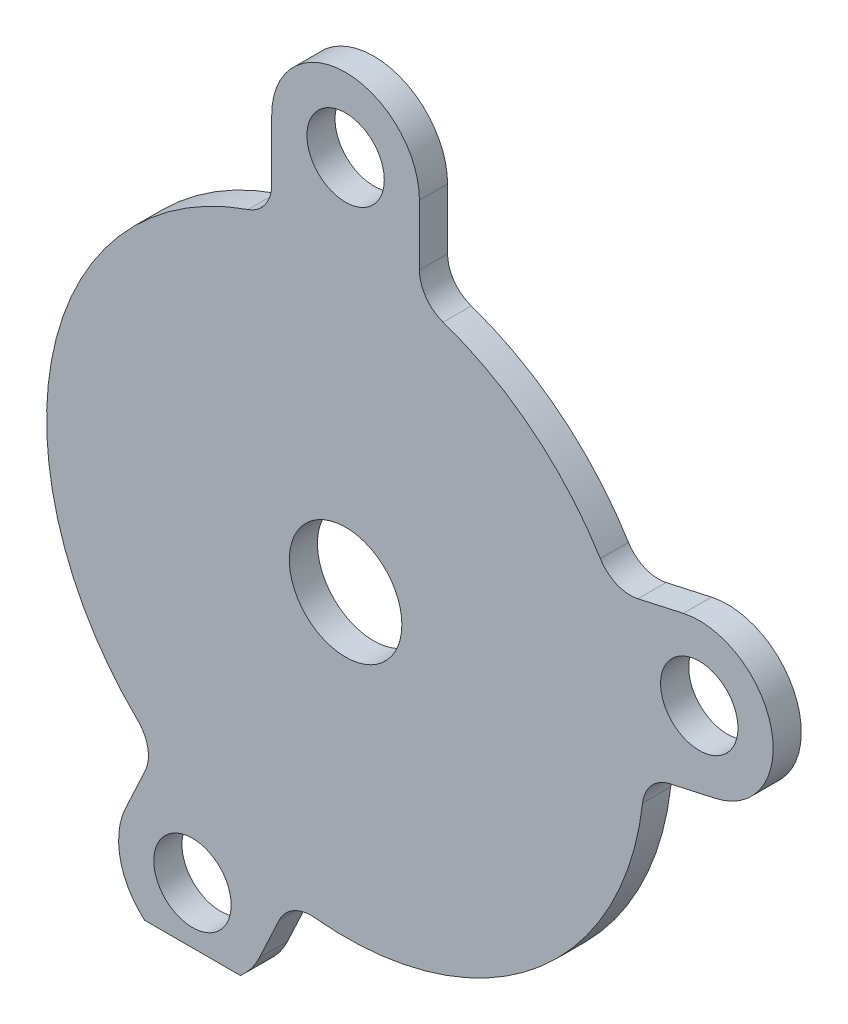
SolidWorks part; units mm, degrees
ref_plane "Front Plane" through (0, 0, 0) normal (0, 0, 1) x (1, 0, 0)
ref_plane "Top Plane" through (0, 0, 0) normal (0, 1, 0) x (1, 0, 0)
ref_plane "Right Plane" through (0, 0, 0) normal (1, 0, 0) x (0, 0, -1)
sketch "Sketch1" plane through (0, 0, 0) normal (0, 0, 1) x (1, 0, 0)
  line L0 (0, 0) -> (90.5096, 20.0655) construction
  line L1 (0, 0) -> (-35.1485, -75.3763) construction
  line L2 (0, 0) -> (0, 66.1304) construction
  line L3 (-31.2811, -42.2374) -> (-28.4917, -36.2556)
  line L4 (-12.2486, -51.1123) -> (-9.4593, -45.1306)
  line L5 (-28.5656, -54.6749) -> (-14.9641, -54.6749)
  line L6 (46.1082, -0.533) -> (52.5519, 0.8955)
  line L7 (48.0066, 21.3977) -> (41.563, 19.9692)
  line L8 (48.0066, 21.3977) -> (50.2792, 11.1466) construction
  line L9 (50.2792, 11.1466) -> (52.5519, 0.8955) construction
  line L10 (-12.4518, 53.5) -> (14.552, 53.5) construction
  line L11 (10.5, 53.5) -> (10.5, 44.8999)
  line L12 (-10.5, 53.5) -> (-10.5, 44.8999)
  circle A0 centre (0, 0) radius 33.5 construction
  arc A1 (-13.8684, 40.1736) -> (-29.5471, -30.5486) centre (0, 0) ccw
  circle A2 centre (50.2792, 11.1466) radius 5.5
  circle A3 centre (0, 53.5) radius 5.5
  circle A4 centre (-21.7648, -46.6749) radius 5.5
  circle A5 centre (0, 0) radius 8
  arc A6 (-4.409, -42.2707) -> (42.223, -4.8445) centre (0, 0) ccw
  arc A7 (10.5, 53.5) -> (-10.5, 53.5) centre (0, 53.5) ccw
  arc A8 (-31.2811, -42.2374) -> (-28.5656, -54.6749) centre (-21.7648, -46.6749) ccw
  arc A9 (36.2196, 22.2348) -> (13.8684, 40.1736) centre (0, 0) ccw
  arc A10 (-14.9641, -54.6749) -> (-12.2486, -51.1123) centre (-21.7648, -46.6749) ccw
  arc A11 (52.5519, 0.8955) -> (48.0066, 21.3977) centre (50.2792, 11.1466) ccw
  arc A12 (46.1082, -0.533) -> (42.223, -4.8445) centre (47.1904, -5.4145) ccw
  arc A13 (41.563, 19.9692) -> (36.2196, 22.2348) centre (40.4808, 24.8507) cw
  arc A14 (10.5, 44.8999) -> (13.8684, 40.1736) centre (15.5, 44.8999) ccw
  arc A15 (-10.5, 44.8999) -> (-13.8684, 40.1736) centre (-15.5, 44.8999) cw
  arc A16 (-28.4917, -36.2556) -> (-29.5471, -30.5486) centre (-33.0233, -34.1425) ccw
  arc A17 (-9.4593, -45.1306) -> (-4.409, -42.2707) centre (-4.9277, -47.2437) cw
  point P33 (37.9337, 19.1646)
  point P42 (-7.8883, -41.7615)
  dimension "D1" = 67
  dimension "D2" = 85
  dimension "D4" = 11
  dimension "D6" = 11
  dimension "D9" = 11
  dimension "D11" = 16
  dimension "D12" = 5
  dimension "D3" = 51.5
  dimension "D5" = 102.5
  dimension "D7" = 53.5
  dimension "D8" = 25
  dimension "D10" = 51.5
  dimension "D13" = 8
extrude "Boss-Extrude1" add sketch "Sketch1" along normal blind 4
